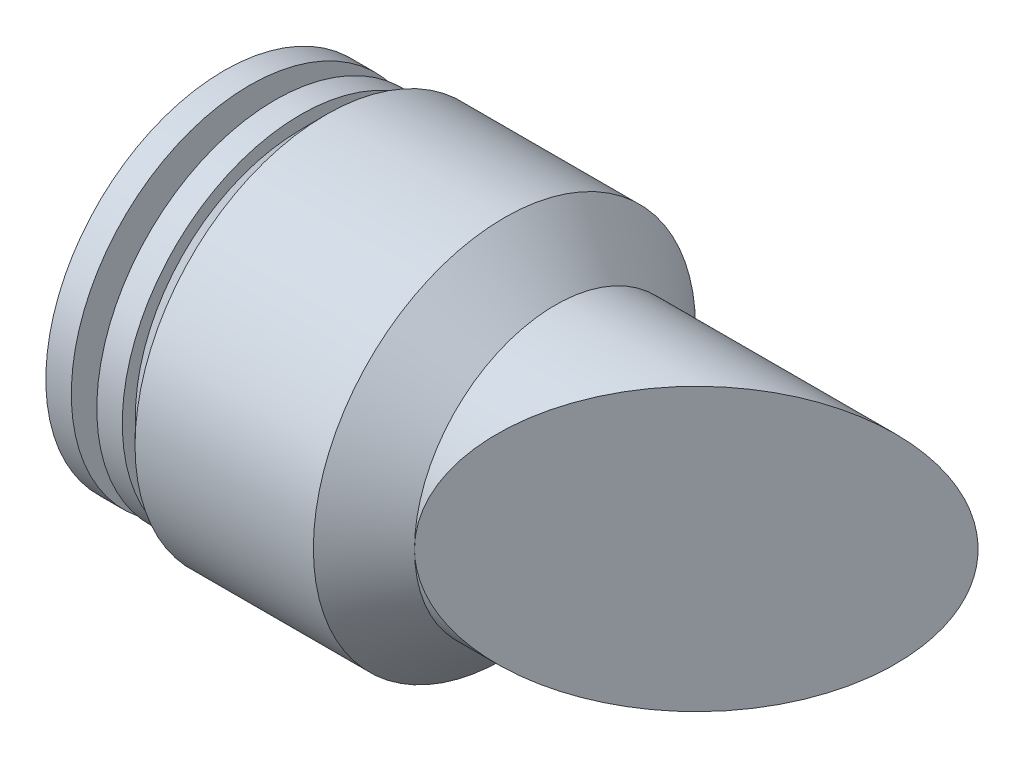
SolidWorks part; units mm, degrees
ref_plane "Спереди" through (0, 0, 0) normal (0, 0, 1) x (1, 0, 0)
ref_plane "Сверху" through (0, 0, 0) normal (0, 1, 0) x (1, 0, 0)
ref_plane "Справа" through (0, 0, 0) normal (1, 0, 0) x (0, 0, -1)
sketch "Эскиз1" plane through (0, 0, 0) normal (0, 0, 1) x (1, 0, 0)
  line L0 (-9.4321, 2.0773) -> (-9.4321, 9.0773)
  line L1 (-9.4321, 9.0773) -> (-8.4321, 9.0773)
  line L2 (-8.4321, 9.0773) -> (-8.4321, 6.0773)
  line L3 (-8.4321, 6.0773) -> (-7.4321, 6.0773)
  line L4 (-7.4321, 6.0773) -> (-7.4321, 9.0773)
  line L5 (-7.4321, 9.0773) -> (-6.4321, 9.0773)
  line L6 (-6.4321, 9.0773) -> (-6.4321, 8.562)
  line L7 (-6.4321, 8.562) -> (-5.4321, 9.5773)
  line L8 (-5.4321, 9.5773) -> (1.5679, 9.5773)
  line L9 (1.5679, 9.5773) -> (3.5679, 7.6073)
  line L10 (3.5679, 7.6073) -> (15.5679, 7.6073)
  line L11 (15.5679, 7.6073) -> (15.5679, 2.0773)
  line L12 (15.5679, 2.0773) -> (-9.4321, 2.0773)
  dimension "D1" = 7
  dimension "D2" = 1
  dimension "D3" = 1
  dimension "D4" = 1
  dimension "D5" = 1
  dimension "D6" = 7
  dimension "D7" = 2
  dimension "D8" = 12
  dimension "D9" = 5.53
  dimension "D10" = 4
  dimension "D11" = 7
  dimension "D12" = 7.5
revolve "Повернуть1" add sketch "Эскиз1" angle 360 about L12
sketch "Эскиз2" plane through (-9.4321, 0, 0) normal (-1, 0, 0) x (0, 0, 1)
  circle A0 centre (0, 2.0773) radius 3
extrude "Вырез-Вытянуть1" cut sketch "Эскиз2" against normal blind 6
sketch "Эскиз3" plane through (0, 0, 0) normal (0, 1, 0) x (1, 0, 0)
  line L0 (3.5679, -5.53) -> (14.7489, 5.6509)
  line L1 (14.7489, 5.6509) -> (16.3719, 5.6509)
  line L2 (16.3719, 5.6509) -> (16.3719, -6.8196)
  line L3 (16.3719, -6.8196) -> (3.5679, -5.7892)
  line L4 (3.5679, -5.7892) -> (3.5679, -5.53)
extrude "Вырез-Вытянуть2" cut sketch "Эскиз3" against normal through all both and the other way through all
